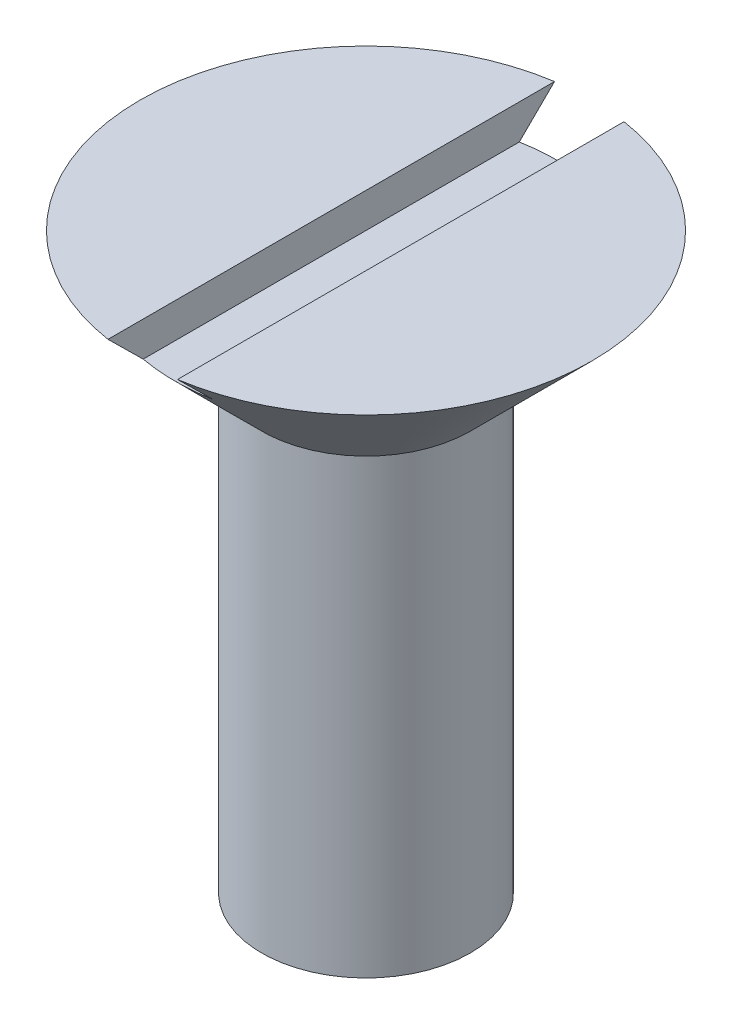
SolidWorks part; units mm, degrees
material "AISI Type A2 Tool Steel"
ref_plane "Front Plane" through (0, 0, 0) normal (0, 0, 1) x (1, 0, 0)
ref_plane "Top Plane" through (0, 0, 0) normal (0, 1, 0) x (1, 0, 0)
ref_plane "Right Plane" through (0, 0, 0) normal (1, 0, 0) x (0, 0, -1)
sketch "Sketch1" plane through (0, 0, 0) normal (0, 0, 1) x (1, 0, 0)
  line L0 (0, 0) -> (0, -18.2321) construction
  line L1 (0, 0) -> (6.5, 0)
  line L2 (6.5, 0) -> (3, -3.5)
  line L3 (3, -3.5) -> (3, -16.5)
  line L4 (3, -16.5) -> (0, -18.2321)
  line L5 (0, 0) -> (0, -18.2321)
  dimension "D1" = 13
  dimension "D2" = 6.5
  dimension "D3" = 45
  dimension "D4" = 3
  dimension "D5" = 60
revolve "Revolve1" add sketch "Sketch1" angle 360 about L0
sketch "Sketch2" plane through (0, 0, 0) normal (0, 0, 1) x (1, 0, 0)
  line L1 (-1, 1) -> (1, 1)
  line L2 (-1, 1) -> (-1, -1)
  line L3 (-1, -1) -> (1, -1)
  line L4 (1, 1) -> (1, -1)
  line L5 (-1, 1) -> (1, -1) construction
  line L6 (-1, -1) -> (1, 1) construction
  point P0 (0, 0)
  dimension "D1" = 2
  dimension "D2" = 1
extrude "Cut-Extrude1" cut sketch "Sketch2" against normal mid plane 86 contours L4 L3 L2 L1
